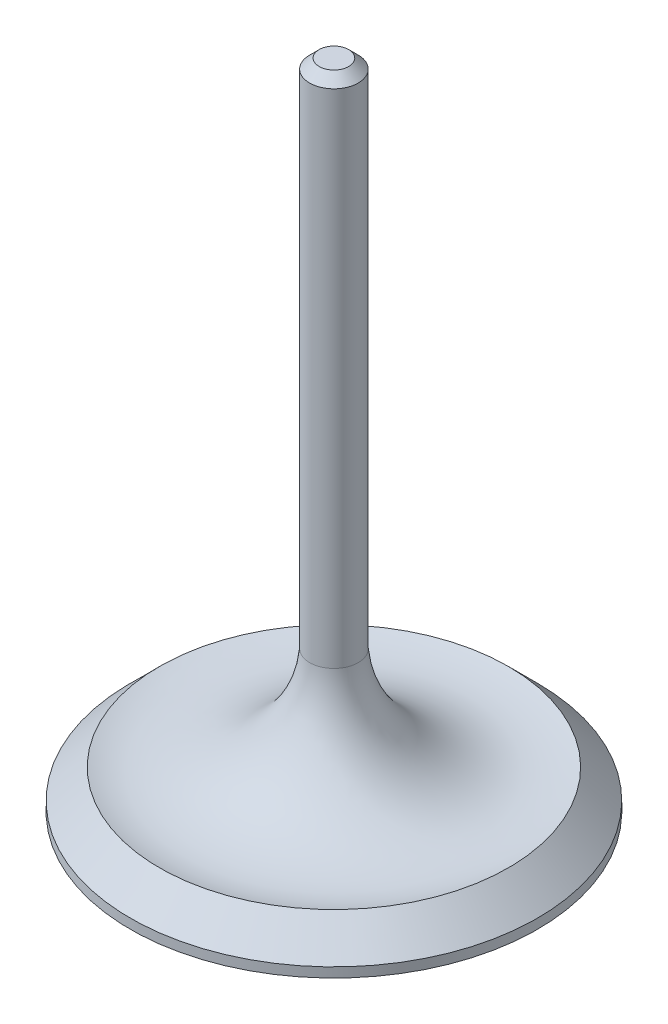
SolidWorks part; units mm, degrees
ref_plane "Front Plane" through (0, 0, 0) normal (0, 0, 1) x (1, 0, 0)
ref_plane "Top Plane" through (0, 0, 0) normal (0, 1, 0) x (1, 0, 0)
ref_plane "Right Plane" through (0, 0, 0) normal (1, 0, 0) x (0, 0, -1)
sketch "Sketch1" plane through (0, 0, 0) normal (1, 0, 0) x (0, 0, -1)
  line L0 (0, 0) -> (0, 85.55)
  line L1 (0, 85.55) -> (3.18, 85.55)
  line L2 (3.18, 85.55) -> (3.18, 18.522)
  line L3 (22.86, 5.08) -> (26.67, 1.27)
  line L4 (26.67, 1.27) -> (26.67, 0)
  line L5 (26.67, 0) -> (0, 0)
  arc A0 (3.18, 18.522) -> (22.86, 5.08) centre (18.3875, 19.6594) ccw
  point P9 (0, 0)
  dimension "D7" = 15.25
  dimension "D1" = 85.55
  dimension "D2" = 26.67
  dimension "D3" = 3.18
  dimension "D4" = 1.27
  dimension "D5" = 3.81
  dimension "D6" = 45
revolve "Revolve1" add sketch "Sketch1" angle 360 about L0
chamfer "Chamfer1" distance 1.25 angle 45 1 edges at (0, 85.55, -3.18)
